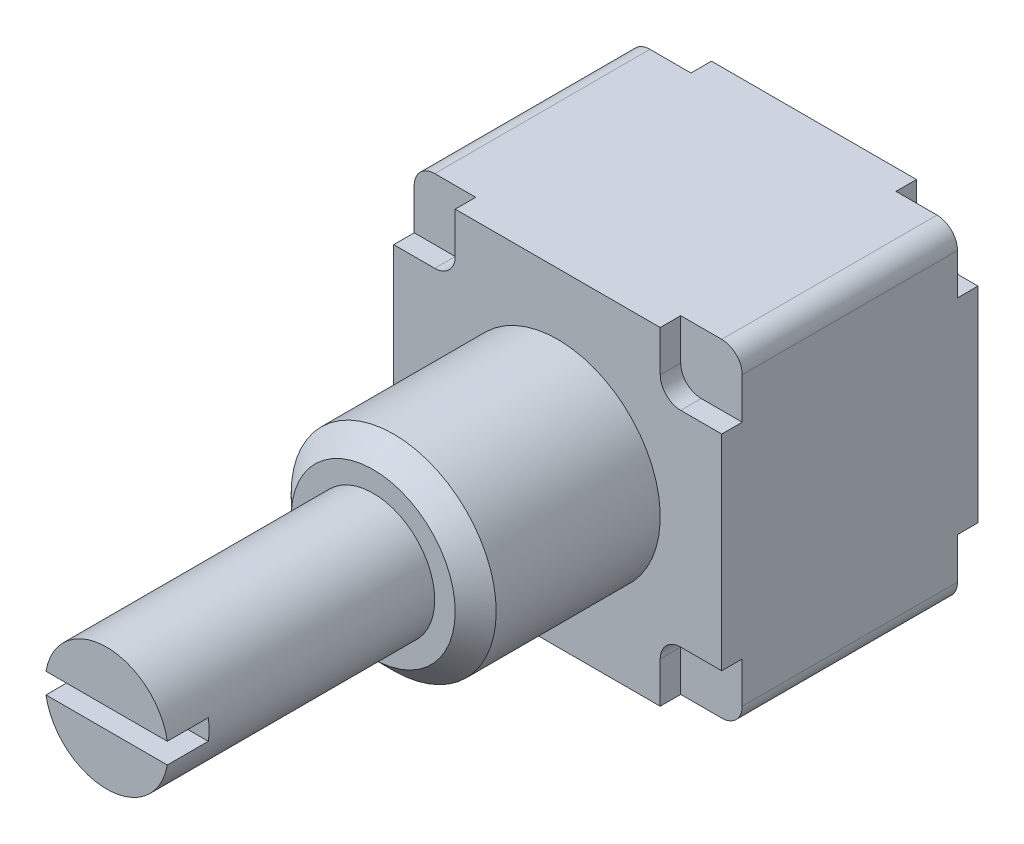
SolidWorks part; units mm, degrees
ref_plane "Plan de face" through (0, 0, 0) normal (0, 0, 1) x (1, 0, 0)
ref_plane "Plan de dessus" through (0, 0, 0) normal (0, 1, 0) x (1, 0, 0)
ref_plane "Plan de droite" through (0, 0, 0) normal (1, 0, 0) x (0, 0, -1)
sketch "Esquisse1" plane through (0, 0, 0) normal (0, 0, 1) x (1, 0, 0)
  line L1 (0, 0) -> (16, 0)
  line L2 (0, 0) -> (0, 16)
  line L3 (0, 16) -> (16, 16)
  line L4 (16, 0) -> (16, 16)
  dimension "D1" = 16
  dimension "D2" = 16
extrude "Extrusion1" add sketch "Esquisse1" along normal blind 12.5
fillet "Congé1" radius 1 4 edges at (16, 0, 6.25) (0, 0, 6.25) (16, 16, 6.25) (0, 16, 6.25)
sketch "Esquisse2" plane through (0, 0, 12.5) normal (0, 0, 1) x (1, 0, 0)
  line L0 (0, 8) -> (16, 8) construction
  line L1 (0, 15) -> (0, 1) construction
  line L2 (16, 1) -> (16, 15) construction
  circle A0 centre (8, 8) radius 5
  dimension "D1" = 10
extrude "Extrusion2" add sketch "Esquisse2" along normal blind 9
cosmetic thread "Représentation de filetage1" parameters "D1"=9, "D2"=9
chamfer "Chanfrein1" distance 1 angle 45 1 edges at (13, 8, 21.5)
sketch "Esquisse3" plane through (0, 0, 21.5) normal (0, 0, 1) x (1, 0, 0)
  circle A0 centre (8, 8) radius 3
  dimension "D1" = 6
extrude "Extrusion3" add sketch "Esquisse3" along normal blind 13
sketch "Esquisse4" plane through (0, 0, 34.5) normal (0, 0, 1) x (1, 0, 0)
  line L0 (8, 8) -> (14.8398, 8) construction
  line L1 (4.6023, 8.5) -> (11.5975, 8.5)
  line L2 (4.6023, 8.5) -> (4.6023, 7.5)
  line L3 (4.6023, 7.5) -> (11.5975, 7.5)
  line L4 (11.5975, 8.5) -> (11.5975, 7.5)
  dimension "D1" = 1
extrude "Enlèv. mat.-Extru.1" cut sketch "Esquisse4" against normal blind 2
sketch "Esquisse5" plane through (0, 0, 12.5) normal (0, 0, 1) x (1, 0, 0)
  line L0 (8, 16) -> (8, 0) construction
  line L1 (15, 16) -> (1, 16) construction
  line L2 (1, 0) -> (15, 0) construction
  line L3 (16, 8) -> (0, 8) construction
  line L4 (16, 1) -> (16, 15) construction
  line L5 (0, 15) -> (0, 1) construction
  line L6 (13, 17.6785) -> (13, 14)
  line L7 (-0.8069, 17.6785) -> (3, 17.6785)
  line L8 (-0.8069, 17.6785) -> (-0.8069, 13)
  line L9 (-0.8069, 13) -> (2, 13)
  line L10 (3, 17.6785) -> (3, 14)
  line L11 (16.8069, 13) -> (14, 13)
  line L12 (16.8069, 17.6785) -> (16.8069, 13)
  line L13 (16.8069, 17.6785) -> (13, 17.6785)
  line L14 (16.8069, -1.6785) -> (13, -1.6785)
  line L15 (16.8069, -1.6785) -> (16.8069, 3)
  line L16 (16.8069, 3) -> (14, 3)
  line L17 (3, -1.6785) -> (3, 2)
  line L18 (-0.8069, 3) -> (2, 3)
  line L19 (-0.8069, -1.6785) -> (-0.8069, 3)
  line L20 (-0.8069, -1.6785) -> (3, -1.6785)
  line L21 (13, -1.6785) -> (13, 2)
  arc A0 (2, 13) -> (3, 14) centre (2, 14) ccw
  arc A1 (14, 13) -> (13, 14) centre (14, 14) cw
  arc A2 (14, 3) -> (13, 2) centre (14, 2) ccw
  arc A3 (2, 3) -> (3, 2) centre (2, 2) cw
  dimension "D3" = 1
  dimension "D1" = 3
  dimension "D2" = 3
extrude "Enlèv. mat.-Extru.2" cut sketch "Esquisse5" against normal blind 1
sketch "Esquisse6" plane through (0, 0, 0) normal (0, 0, -1) x (-1, 0, 0)
  line L4 (0, 13) -> (0, 15)
  line L5 (-2, 13) -> (0, 13)
  line L6 (-3, 16) -> (-3, 14)
  line L7 (-1, 16) -> (-3, 16)
  line L8 (0, 13) -> (0, 15)
  line L9 (-2, 13) -> (0, 13)
  line L10 (-3, 16) -> (-3, 14)
  line L11 (-1, 16) -> (-3, 16)
  line L12 (-13, 16) -> (-15, 16)
  line L13 (-13, 14) -> (-13, 16)
  line L14 (-16, 13) -> (-14, 13)
  line L15 (-16, 15) -> (-16, 13)
  line L16 (-13, 16) -> (-15, 16)
  line L17 (-13, 14) -> (-13, 16)
  line L18 (-16, 13) -> (-14, 13)
  line L19 (-16, 15) -> (-16, 13)
  line L20 (-3, 0) -> (-1, 0)
  line L21 (-3, 2) -> (-3, 0)
  line L22 (0, 3) -> (-2, 3)
  line L23 (0, 1) -> (0, 3)
  line L24 (-3, 0) -> (-1, 0)
  line L25 (-3, 2) -> (-3, 0)
  line L26 (0, 3) -> (-2, 3)
  line L27 (0, 1) -> (0, 3)
  line L28 (-15, 0) -> (-13, 0)
  line L29 (-16, 3) -> (-16, 1)
  line L30 (-14, 3) -> (-16, 3)
  line L31 (-13, 0) -> (-13, 2)
  line L32 (-15, 0) -> (-13, 0)
  line L33 (-16, 3) -> (-16, 1)
  line L34 (-14, 3) -> (-16, 3)
  line L35 (-13, 0) -> (-13, 2)
  arc A2 (-3, 14) -> (-2, 13) centre (-2, 14) ccw
  arc A3 (0, 15) -> (-1, 16) centre (-1, 15) ccw
  arc A4 (-3, 14) -> (-2, 13) centre (-2, 14) ccw
  arc A5 (0, 15) -> (-1, 16) centre (-1, 15) ccw
  arc A6 (-15, 16) -> (-16, 15) centre (-15, 15) ccw
  arc A7 (-14, 13) -> (-13, 14) centre (-14, 14) ccw
  arc A8 (-15, 16) -> (-16, 15) centre (-15, 15) ccw
  arc A9 (-14, 13) -> (-13, 14) centre (-14, 14) ccw
  arc A10 (-1, 0) -> (0, 1) centre (-1, 1) ccw
  arc A11 (-2, 3) -> (-3, 2) centre (-2, 2) ccw
  arc A12 (-1, 0) -> (0, 1) centre (-1, 1) ccw
  arc A13 (-2, 3) -> (-3, 2) centre (-2, 2) ccw
  arc A14 (-16, 1) -> (-15, 0) centre (-15, 1) ccw
  arc A15 (-13, 2) -> (-14, 3) centre (-14, 2) ccw
  arc A16 (-16, 1) -> (-15, 0) centre (-15, 1) ccw
  arc A17 (-13, 2) -> (-14, 3) centre (-14, 2) ccw
  dimension "D1" = 0
  dimension "D2" = 0
  dimension "D3" = 0
  dimension "D4" = 0
extrude "Enlèv. mat.-Extru.3" cut sketch "Esquisse6" against normal blind 1
